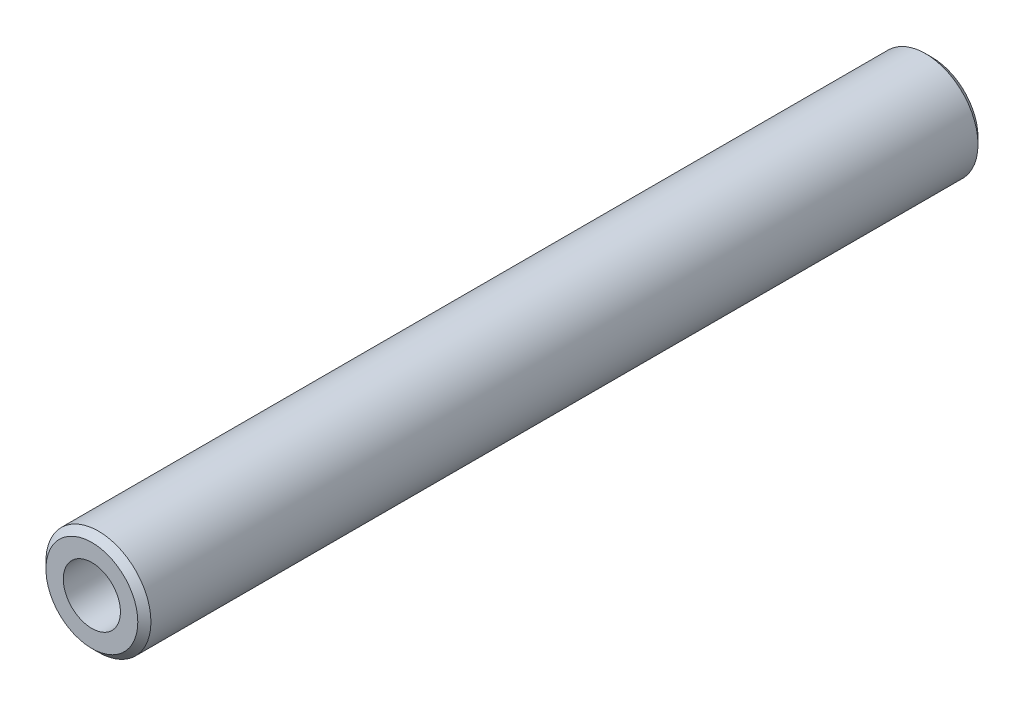
SolidWorks part; units mm, degrees
material "Alloy Steel (SS)"
ref_plane "Front Plane" through (0, 0, 0) normal (0, 0, 1) x (1, 0, 0)
ref_plane "Top Plane" through (0, 0, 0) normal (0, 1, 0) x (1, 0, 0)
ref_plane "Right Plane" through (0, 0, 0) normal (1, 0, 0) x (0, 0, -1)
sketch "Sketch1" plane through (0, 0, 0) normal (0, 0, 1) x (1, 0, 0)
  circle A0 centre (0, 0) radius 3.175
  dimension "D1" = 6.35
extrude "Boss-Extrude1" add sketch "Sketch1" along normal mid plane 50.8
hole_wizard "Tap Drill for #8-32 Tap1" positions "3DSketch1" profile "Sketch5" hole size "#8-32" standard "ANSI Inch"
sketch3d "3DSketch1"
  line L0 (0, 0, 25.4) -> (0, 0, -25.4) construction
  point P0 (0, 0, 25.4)
  point P4 (0, 0, -25.4)
sketch "Sketch5" plane through (0, 0, 25.4) normal (1, 0, 0) x (0, -1, 0)
  line L0 (0, 0) -> (0, 7.3878)
  line L1 (0, 7.3878) -> (1.7272, 6.35)
  line L2 (1.7272, 6.35) -> (1.7272, 0)
  line L5 (1.7272, 0) -> (0, 0)
  line L10 (0, 7.3878) -> (-1.7272, 6.35) construction
  line L11 (0, -6.35) -> (0, 107.95) construction
  dimension "Hole Dia." = 3.4544
  dimension "Hole Depth" = 6.35
  dimension "Drill Angle" = 118
chamfer "Chamfer1" distance 0.3969 angle 45 2 edges at (3.175, 0, -25.4) (3.175, 0, 25.4)
